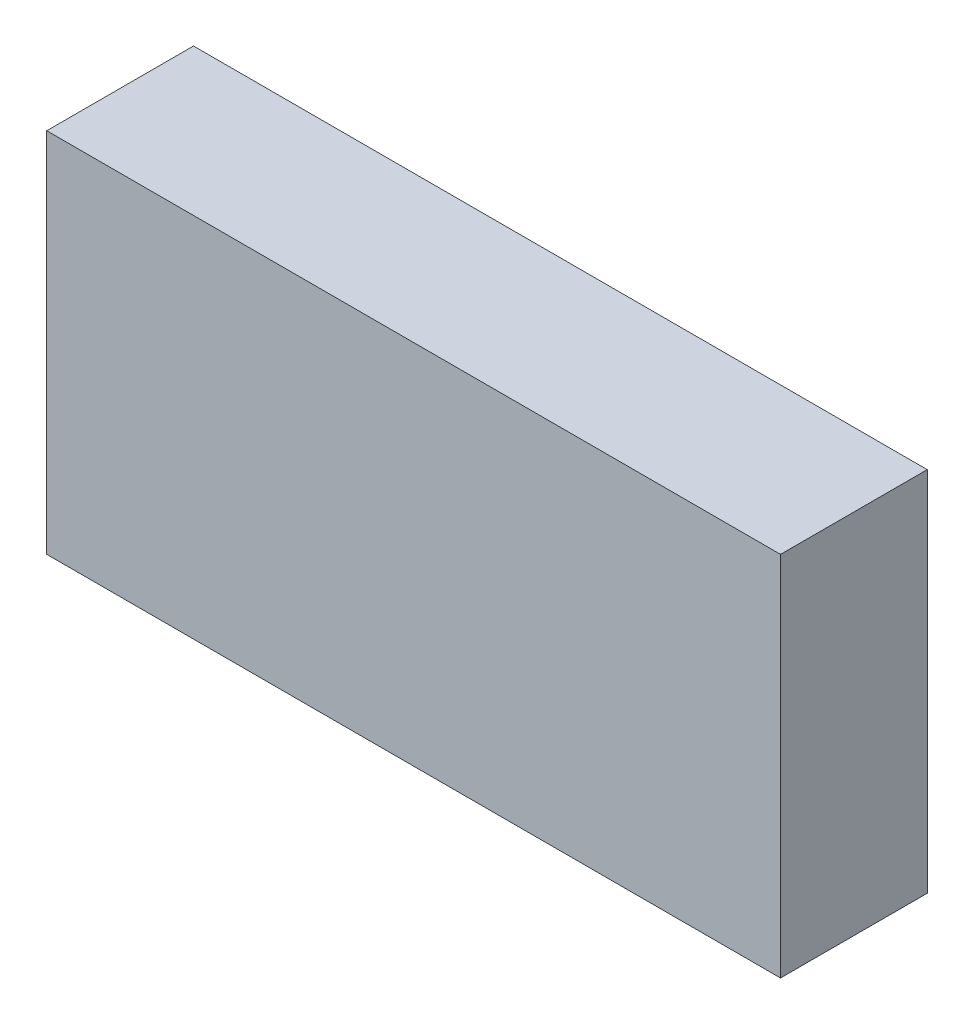
SolidWorks part; units mm, degrees
ref_plane "Front Plane" through (0, 0, 0) normal (0, 0, 1) x (1, 0, 0)
ref_plane "Top Plane" through (0, 0, 0) normal (0, 1, 0) x (1, 0, 0)
ref_plane "Right Plane" through (0, 0, 0) normal (1, 0, 0) x (0, 0, -1)
sketch "Sketch1" plane through (0, 0, 0) normal (0, 0, 1) x (1, 0, 0)
  line L1 (-31.6279, 18.314) -> (18.3721, 18.314)
  line L2 (-31.6279, 18.314) -> (-31.6279, -6.686)
  line L3 (-31.6279, -6.686) -> (18.3721, -6.686)
  line L4 (18.3721, 18.314) -> (18.3721, -6.686)
  point P4 (18.3721, 5.814)
  dimension "D1" = 50
  dimension "D2" = 25
extrude "Boss-Extrude1" add sketch "Sketch1" along normal blind 10
